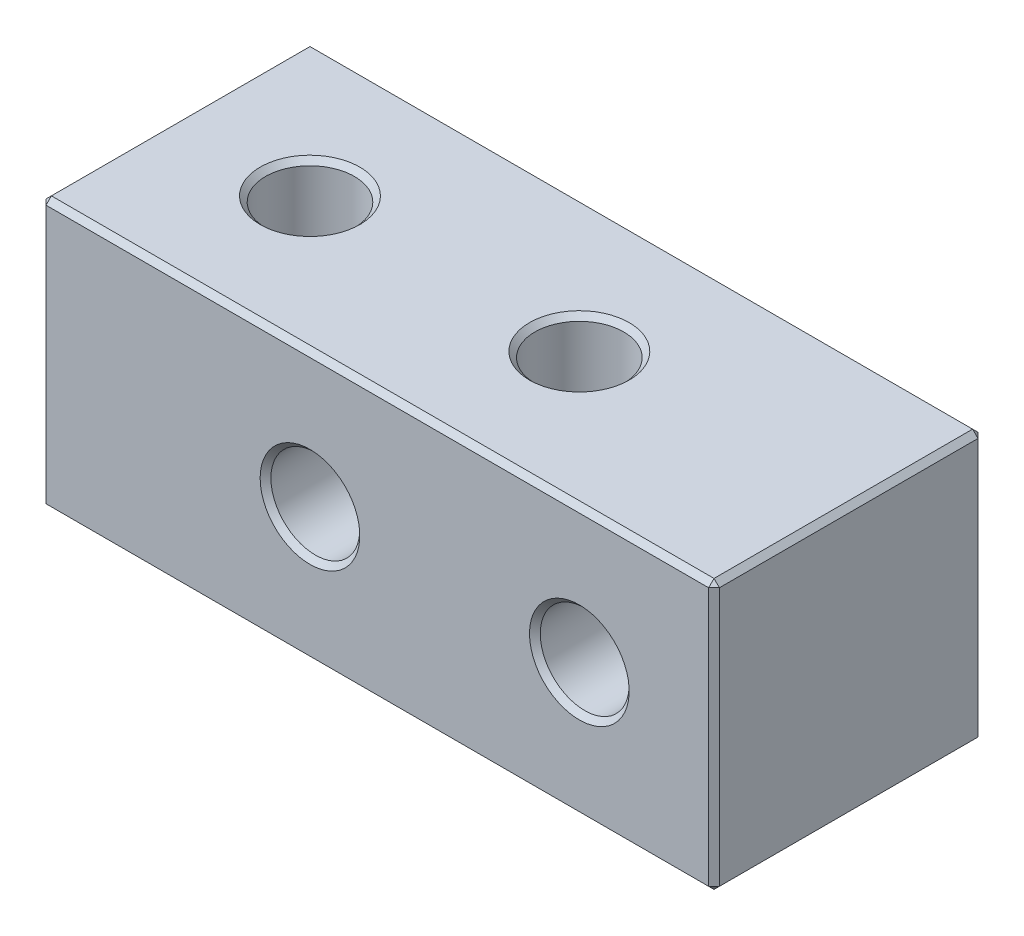
SolidWorks part; units mm, degrees
ref_plane "前视基准面" through (0, 0, 0) normal (0, 0, 1) x (1, 0, 0)
ref_plane "上视基准面" through (0, 0, 0) normal (0, 1, 0) x (1, 0, 0)
ref_plane "右视基准面" through (0, 0, 0) normal (1, 0, 0) x (0, 0, -1)
sketch "草图1" plane through (0, 0, 0) normal (0, 1, 0) x (1, 0, 0)
  line L1 (-12.5, 5) -> (12.5, 5)
  line L2 (-12.5, 5) -> (-12.5, -5)
  line L3 (-12.5, -5) -> (12.5, -5)
  line L4 (12.5, 5) -> (12.5, -5)
  line L5 (-12.5, 5) -> (12.5, -5) construction
  line L6 (-12.5, -5) -> (12.5, 5) construction
  point P0 (0, 0)
  dimension "D1" = 10
  dimension "D2" = 25
extrude "凸台-拉伸1" add sketch "草图1" along normal mid plane 10
hole_wizard "M4 螺纹孔1" positions "草图4" profile "草图6" tap size "M4" standard "GB" end condition through all
sketch "草图4" plane through (0, 5, 0) normal (0, 1, 0) x (1, 0, 0)
  line L0 (-12.5, 5) -> (-12.5, -5) construction
  line L1 (0, 0) -> (-50000, 0) construction
  point P0 (-7.5, 0)
  point P2 (2.5, 0)
  dimension "D1" = 5
  dimension "D2" = 10
sketch "草图6" plane through (-7.5, 5, 0) normal (1, 0, 0) x (0, 0, 1)
  line L0 (0, 0) -> (0, 10)
  line L1 (0, 10) -> (1.65, 10)
  line L2 (1.65, 10) -> (1.65, 0)
  line L5 (1.65, 0) -> (0, 0)
  line L11 (0, -6.35) -> (0, 107.95) construction
  dimension "通孔螺纹孔钻头直径" = 3.3
  dimension "通孔螺纹孔钻头深度" = 10
cosmetic thread "孔螺蚊线1" parameters "D2"=4
cosmetic thread "孔螺蚊线5" parameters "D2"=4
hole_wizard "M4 螺纹孔2" positions "草图7" profile "草图8" tap size "M4" standard "GB" end condition through all
sketch "草图7" plane through (0, 0, -5) normal (0, 0, -1) x (-1, 0, 0)
  line L0 (0, 0) -> (-50000, 0) construction
  line L1 (-12.5, 5) -> (-12.5, -5) construction
  point P0 (-7.5, 0)
  point P2 (2.5, 0)
  dimension "D1" = 5
  dimension "D2" = 10
sketch "草图8" plane through (7.5, 0, -5) normal (1, 0, 0) x (0, 1, 0)
  line L0 (0, 0) -> (0, 10)
  line L1 (0, 10) -> (1.65, 10)
  line L2 (1.65, 10) -> (1.65, 0)
  line L5 (1.65, 0) -> (0, 0)
  line L11 (0, -6.35) -> (0, 107.95) construction
  dimension "通孔螺纹孔钻头直径" = 3.3
  dimension "通孔螺纹孔钻头深度" = 10
cosmetic thread "孔螺蚊线3" parameters "D2"=4
cosmetic thread "孔螺蚊线4" parameters "D2"=4
chamfer "倒角1" distance 0.2 angle 45 20 edges at (2.5, -5, 1.65) (-7.5, -5, 1.65) (-4.15, 0, 5) (5.85, 0, 5) (2.5, 5, 1.65) (-7.5, 5, 1.65) (-12.5, -5, 0) (12.5, -5, 0) (-12.5, 0, 5) (0, -5, 5) (12.5, 0, 5) (0, 5, 5) (-12.5, 5, 0) (12.5, 5, 0) (12.5, 0, -5) (0, 5, -5) (-12.5, 0, -5) (0, -5, -5) (-4.15, 0, -5) (5.85, 0, -5)
